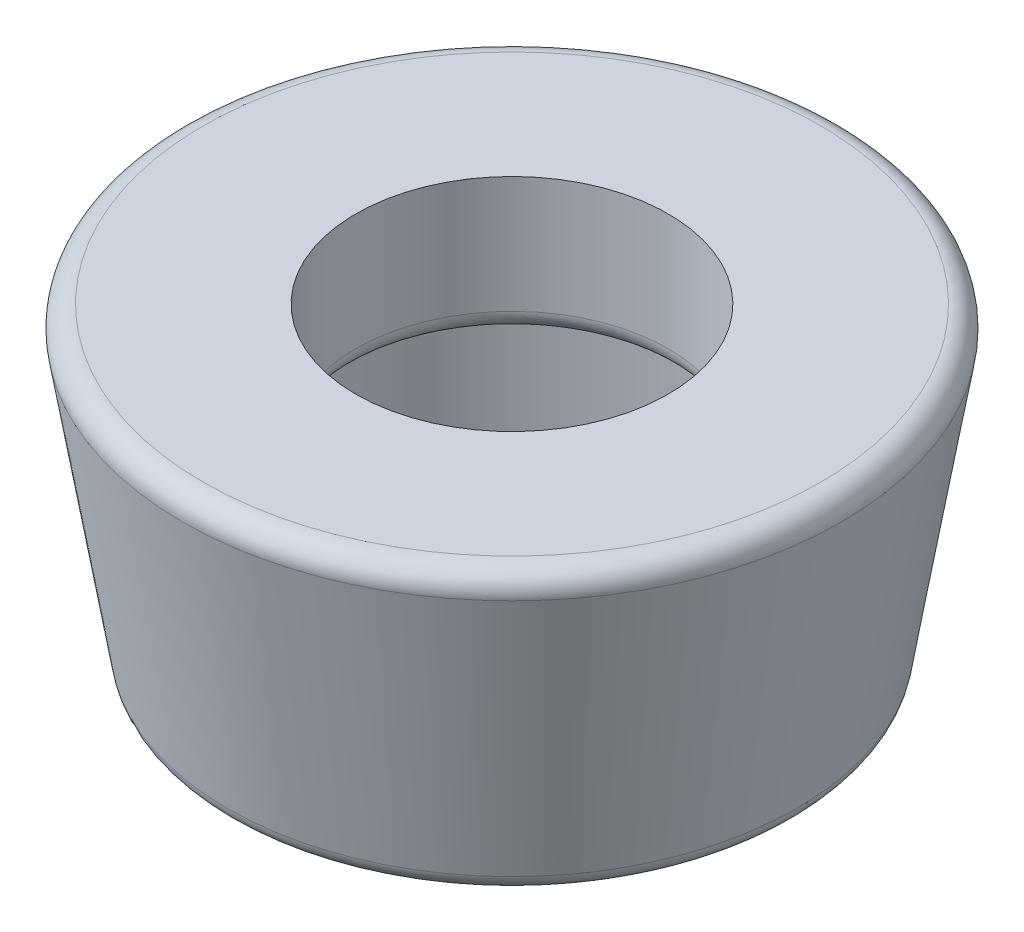
SolidWorks part; units mm, degrees
ref_plane "Front Plane" through (0, 0, 0) normal (0, 0, 1) x (1, 0, 0)
ref_plane "Top Plane" through (0, 0, 0) normal (0, 1, 0) x (1, 0, 0)
ref_plane "Right Plane" through (0, 0, 0) normal (1, 0, 0) x (0, 0, -1)
sketch "Sketch1" plane through (0, 0, 0) normal (0, 0, 1) x (1, 0, 0)
  line L0 (1.5, 0) -> (2.9639, 0)
  line L1 (3.1612, -0.2329) -> (2.7279, -2.8329)
  line L2 (2.5306, -3) -> (2.2, -3)
  line L3 (0, 1.9554) -> (0, -4.2149) construction
  line L4 (1.5, 0) -> (1.5, -1.1213)
  line L5 (1.7, -1.3213) -> (2.2, -1.3213)
  line L6 (2.2, -1.3213) -> (2.2, -3)
  arc A0 (1.5, -1.1213) -> (1.7, -1.3213) centre (1.7, -1.1213) ccw
  arc A1 (2.7279, -2.8329) -> (2.5306, -3) centre (2.5306, -2.8) cw
  arc A2 (2.9639, 0) -> (3.1612, -0.2329) centre (2.9639, -0.2) cw
  dimension "D1" = 0.2
revolve "Revolve1" add sketch "Sketch1" angle 360 about L3
